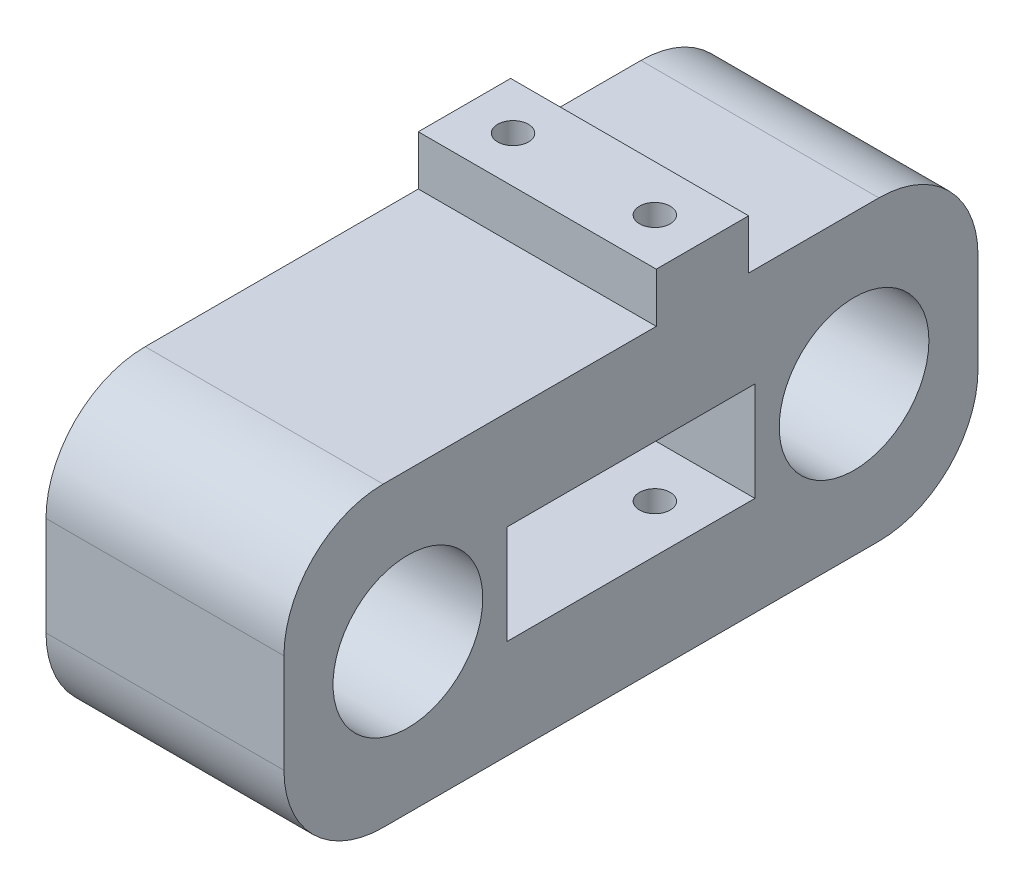
SolidWorks part; units mm, degrees
ref_plane "前视基准面" through (0, 0, 0) normal (0, 0, 1) x (1, 0, 0)
ref_plane "上视基准面" through (0, 0, 0) normal (0, 1, 0) x (1, 0, 0)
ref_plane "右视基准面" through (0, 0, 0) normal (1, 0, 0) x (0, 0, -1)
sketch "草图1" plane through (0, 0, 0) normal (0, 1, 0) x (1, 0, 0)
  line L1 (8.2419, 10.5227) -> (32.2419, 10.5227)
  line L2 (8.2419, 10.5227) -> (8.2419, -59.4773)
  line L3 (8.2419, -59.4773) -> (32.2419, -59.4773)
  line L4 (32.2419, 10.5227) -> (32.2419, -59.4773)
  line L5 (8.2419, 10.5227) -> (32.2419, -59.4773) construction
  line L6 (8.2419, -59.4773) -> (32.2419, 10.5227) construction
  point P4 (20.2419, -24.4773)
  dimension "D1" = 24
  dimension "D2" = 70
extrude "凸台-拉伸1" add sketch "草图1" along normal blind 30
sketch "草图2" plane through (32.2419, 0, 0) normal (1, 0, 0) x (0, 0, -1)
  line L0 (-24.4773, 0) -> (-24.4773, 30) construction
  line L1 (-59.4773, 0) -> (10.5227, 0) construction
  line L2 (-59.4773, 30) -> (10.5227, 30) construction
  line L3 (-59.4773, 15) -> (10.5227, 15) construction
  line L4 (-59.4773, 30) -> (-59.4773, 0) construction
  line L5 (10.5227, 30) -> (10.5227, 0) construction
  circle A0 centre (-46.9773, 15) radius 7.55
  circle A1 centre (-1.9773, 15) radius 7.55
  dimension "D1" = 15.1
  dimension "D3" = 12.5
  dimension "D2" = 45
extrude "切除-拉伸1" cut sketch "草图2" against normal through all
sketch "草图3" plane through (32.2419, 0, 0) normal (1, 0, 0) x (0, 0, -1)
  line L1 (-36.9773, 20) -> (-11.9773, 20)
  line L2 (-36.9773, 20) -> (-36.9773, 10)
  line L3 (-36.9773, 10) -> (-11.9773, 10)
  line L4 (-11.9773, 20) -> (-11.9773, 10)
  line L5 (-36.9773, 20) -> (-11.9773, 10) construction
  line L6 (-36.9773, 10) -> (-11.9773, 20) construction
  point P4 (-24.4773, 15)
extrude "切除-拉伸2" cut sketch "草图3" against normal through all
sketch "草图4" plane through (0, 30, 0) normal (0, 1, 0) x (1, 0, 0)
  line L0 (8.2419, -12.6108) -> (8.2419, -21.9283)
  line L1 (8.2419, 10.5227) -> (8.2419, -59.4773) construction
  line L2 (8.2419, -21.9283) -> (32.2419, -21.9283)
  line L3 (32.2419, -59.4773) -> (32.2419, 10.5227) construction
  line L4 (32.2419, -21.9283) -> (32.2419, -12.6108)
  line L5 (32.2419, -12.6108) -> (8.2419, -12.6108)
extrude "凸台-拉伸2" add sketch "草图4" along normal blind 5
sketch "草图5" plane through (0, 35, 0) normal (0, 1, 0) x (1, 0, 0)
  line L0 (32.2419, -17.2696) -> (8.2419, -17.2696) construction
  line L2 (32.2419, -21.9283) -> (32.2419, -12.6108) construction
  line L3 (8.2419, -12.6108) -> (8.2419, -21.9283) construction
  circle A0 centre (27.4412, -17.2696) radius 1.55
  circle A1 centre (13.1412, -17.2696) radius 1.55
  dimension "D1" = 3.1
  dimension "D2" = 3.1
  dimension "D3" = 14.3
extrude "切除-拉伸3" cut sketch "草图5" against normal blind 31
fillet "圆角1" radius 10 4 edges at (20.2419, 0, 59.4773) (20.2419, 30, 59.4773) (20.2419, 0, -10.5227) (20.2419, 30, -10.5227)
